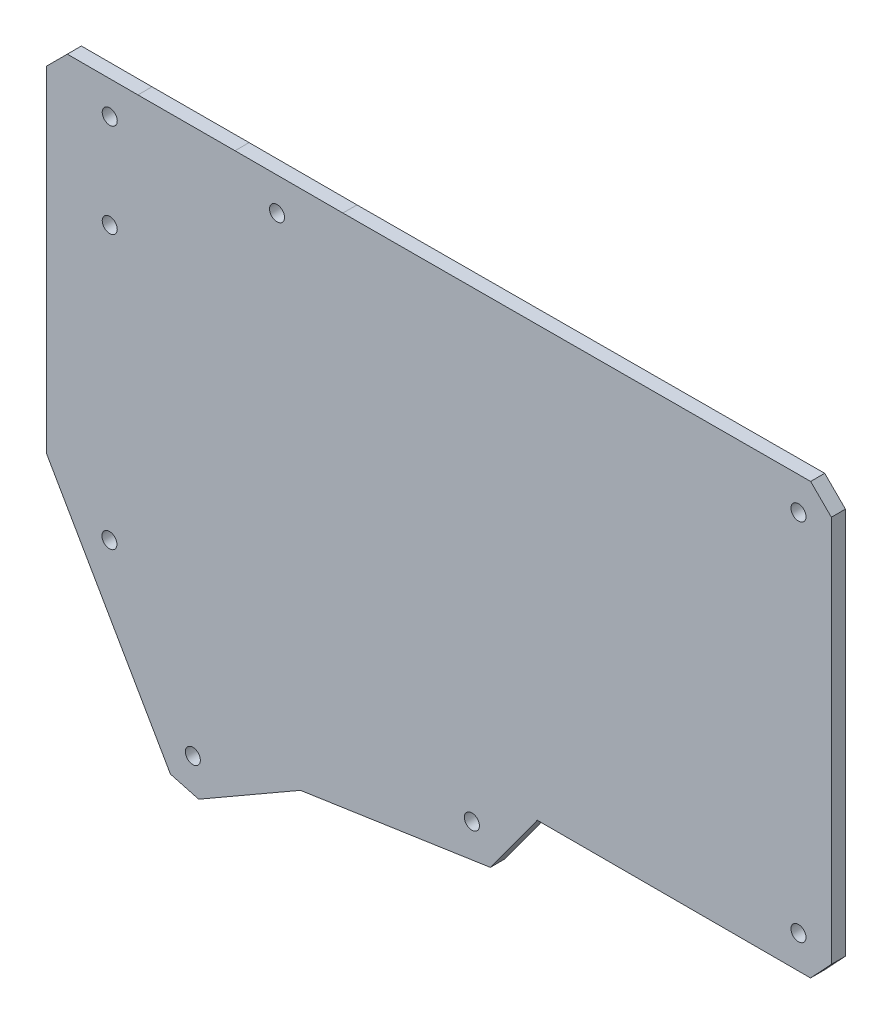
SolidWorks part; units mm, degrees
ref_plane "Plan de face" through (0, 0, 0) normal (0, 0, 1) x (1, 0, 0)
ref_plane "Plan de dessus" through (0, 0, 0) normal (0, 1, 0) x (1, 0, 0)
ref_plane "Plan de droite" through (0, 0, 0) normal (1, 0, 0) x (0, 0, -1)
sketch "Esquisse1" plane through (0, 0, 0) normal (0, 0, 1) x (1, 0, 0)
  line L0 (-117.3419, -15.4198) -> (-103.3409, -15.4198) construction
  line L1 (-103.3409, -15.4198) -> (-103.3409, -29.4208) construction
  line L2 (-103.3409, -29.4208) -> (-117.3419, -29.4208) construction
  line L3 (-117.3419, -29.4208) -> (-117.3419, -15.4198) construction
  line L4 (-98.3406, -27.0457) -> (-98.3406, -13.0447) construction
  line L5 (-98.3406, -13.0447) -> (-84.3396, -13.0447) construction
  line L6 (-84.3396, -13.0447) -> (-84.3396, -27.0457) construction
  line L7 (-84.3396, -27.0457) -> (-98.3406, -27.0457) construction
  line L8 (-79.3392, -24.6705) -> (-79.3392, -10.6695) construction
  line L9 (-79.3392, -10.6695) -> (-65.3382, -10.6695) construction
  line L10 (-65.3382, -10.6695) -> (-65.3382, -24.6705) construction
  line L11 (-65.3382, -24.6705) -> (-79.3392, -24.6705) construction
  line L12 (-60.3379, -27.0457) -> (-60.3379, -13.0447) construction
  line L13 (-60.3379, -13.0447) -> (-46.3369, -13.0447) construction
  line L14 (-46.3369, -13.0447) -> (-46.3369, -27.0457) construction
  line L15 (-46.3369, -27.0457) -> (-60.3379, -27.0457) construction
  line L16 (-41.3365, -31.796) -> (-41.3365, -17.795) construction
  line L17 (-41.3365, -17.795) -> (-27.3355, -17.795) construction
  line L18 (-27.3355, -17.795) -> (-27.3355, -31.796) construction
  line L19 (-27.3355, -31.796) -> (-41.3365, -31.796) construction
  line L20 (-22.3347, -31.796) -> (-22.3347, -17.795) construction
  line L21 (-22.3347, -17.795) -> (-8.3337, -17.795) construction
  line L22 (-8.3337, -17.795) -> (-8.3337, -31.796)
  line L23 (-8.3337, -31.796) -> (-22.3347, -31.796) construction
  line L24 (-117.3419, -34.4212) -> (-103.3409, -34.4212) construction
  line L25 (-103.3409, -34.4212) -> (-103.3409, -48.4222) construction
  line L26 (-103.3409, -48.4222) -> (-117.3419, -48.4222) construction
  line L27 (-117.3419, -48.4222) -> (-117.3419, -34.4212) construction
  line L28 (-98.3406, -32.046) -> (-84.3396, -32.046) construction
  line L29 (-84.3396, -32.046) -> (-84.3396, -46.047) construction
  line L30 (-84.3396, -46.047) -> (-98.3406, -46.047) construction
  line L31 (-98.3406, -46.047) -> (-98.3406, -32.046) construction
  line L32 (-79.3392, -29.6709) -> (-65.3382, -29.6709) construction
  line L33 (-65.3382, -29.6709) -> (-65.3382, -43.6718) construction
  line L34 (-65.3382, -43.6718) -> (-79.3392, -43.6718) construction
  line L35 (-79.3392, -43.6718) -> (-79.3392, -29.6709) construction
  line L36 (-60.3379, -32.046) -> (-46.3369, -32.046) construction
  line L37 (-46.3369, -32.046) -> (-46.3369, -46.047) construction
  line L38 (-46.3369, -46.047) -> (-60.3379, -46.047) construction
  line L39 (-60.3379, -46.047) -> (-60.3379, -32.046) construction
  line L40 (-41.3365, -36.7964) -> (-27.3355, -36.7964) construction
  line L41 (-27.3355, -36.7964) -> (-27.3355, -50.7973) construction
  line L42 (-27.3355, -50.7973) -> (-41.3365, -50.7973) construction
  line L43 (-41.3365, -50.7973) -> (-41.3365, -36.7964) construction
  line L44 (-22.3347, -36.7964) -> (-8.3337, -36.7964) construction
  line L45 (-8.3337, -36.7964) -> (-8.3337, -50.7973) construction
  line L46 (-8.3337, -50.7973) -> (-22.3347, -50.7973) construction
  line L47 (-22.3347, -50.7973) -> (-22.3347, -36.7964) construction
  line L48 (-22.3347, -55.7977) -> (-8.3337, -55.7977) construction
  line L49 (-8.3337, -55.7977) -> (-8.3337, -69.7987) construction
  line L50 (-8.3337, -69.7987) -> (-22.3347, -69.7987) construction
  line L51 (-22.3347, -69.7987) -> (-22.3347, -55.7977) construction
  line L52 (-41.3365, -55.7977) -> (-27.3355, -55.7977) construction
  line L53 (-27.3355, -55.7977) -> (-27.3355, -69.7987) construction
  line L54 (-27.3355, -69.7987) -> (-41.3365, -69.7987) construction
  line L55 (-41.3365, -69.7987) -> (-41.3365, -55.7977) construction
  line L56 (-60.3379, -51.0474) -> (-46.3369, -51.0474) construction
  line L57 (-46.3369, -51.0474) -> (-46.3369, -65.0484) construction
  line L58 (-46.3369, -65.0484) -> (-60.3379, -65.0484) construction
  line L59 (-60.3379, -65.0484) -> (-60.3379, -51.0474) construction
  line L60 (-79.3392, -48.6722) -> (-65.3382, -48.6722) construction
  line L61 (-65.3382, -48.6722) -> (-65.3382, -62.6732) construction
  line L62 (-65.3382, -62.6732) -> (-79.3392, -62.6732) construction
  line L63 (-79.3392, -62.6732) -> (-79.3392, -48.6722) construction
  line L64 (-98.3406, -51.0474) -> (-84.3396, -51.0474) construction
  line L65 (-84.3396, -51.0474) -> (-84.3396, -65.0484) construction
  line L66 (-84.3396, -65.0484) -> (-98.3406, -65.0484) construction
  line L67 (-98.3406, -65.0484) -> (-98.3406, -51.0474) construction
  line L68 (-117.3419, -53.4225) -> (-103.3409, -53.4225) construction
  line L69 (-103.3409, -53.4225) -> (-103.3409, -67.4235) construction
  line L70 (-103.3409, -67.4235) -> (-117.3419, -67.4235) construction
  line L71 (-117.3419, -67.4235) -> (-117.3419, -53.4225) construction
  line L72 (-88.8399, -70.6738) -> (-74.8389, -70.6738) construction
  line L73 (-74.8389, -70.6738) -> (-74.8389, -84.6747) construction
  line L74 (-74.8389, -84.6747) -> (-88.8399, -84.6747) construction
  line L75 (-88.8399, -84.6747) -> (-88.8399, -70.6738) construction
  line L76 (-111.4175, -75.4665) -> (-97.8899, -71.8565) construction
  line L77 (-97.8899, -71.8565) -> (-94.28, -85.3841) construction
  line L78 (-94.28, -85.3841) -> (-107.8075, -88.9941) construction
  line L79 (-107.8075, -88.9941) -> (-111.4175, -75.4665) construction
  line L80 (-134.6581, -81.5997) -> (-122.5281, -74.6075) construction
  line L81 (-122.5281, -74.6075) -> (-115.5359, -86.7375) construction
  line L82 (-115.5359, -86.7375) -> (-127.6659, -93.7297) construction
  line L83 (-127.6659, -93.7297) -> (-134.6581, -81.5997) construction
  line L86 (-6.3391, -71.9336) -> (-62.0853, -71.9336) construction
  line L89 (-72.824, -86.6446) -> (-62.0853, -71.9336) construction
  line L96 (-109.7697, -91.4639) -> (-73.0906, -86.6918) construction
  line L97 (-124.664, -99.8297) -> (-110.3971, -91.5881) construction
  line L98 (-139.9408, -76.5013) -> (-126.7151, -99.4281) construction
  line L99 (-119.8527, -15.5421) -> (-139.6028, -15.5421) construction
  line L100 (-100.8528, -13.2921) -> (-118.8527, -13.2921) construction
  line L101 (-63.8455, -8.5421) -> (-80.8528, -8.5421) construction
  line L102 (-44.8455, -10.792) -> (-62.8485, -10.792) construction
  line L103 (-25.8456, -15.5421) -> (-43.8486, -15.5421) construction
  line L104 (-6.8456, -15.5421) -> (-23.8529, -15.5421) construction
  line L105 (-6.2741, -71.3672) -> (-6.2741, -16.1136) construction
  line L106 (-23.8529, -71.9423) -> (-6.8456, -71.9423) construction
  line L107 (-61.8455, -71.9423) -> (-25.8456, -71.9423) construction
  line L108 (-72.6738, -86.4911) -> (-62.1363, -72.0583) construction
  line L109 (-140.1743, -16.1136) -> (-140.1743, -75.5958) construction
  line L110 (-134.3462, 1.5705) -> (-134.3466, -55.7217) construction
  line L111 (-134.3466, -55.7217) -> (-160.479, -70.8411) construction
  line L112 (-160.479, -70.8411) -> (-133.7613, -117.344) construction
  line L113 (-126.937, -119.1852) -> (-105.0783, -106.604) construction
  line L114 (-105.0783, -106.604) -> (-64.4097, -100.5586) construction
  line L115 (-64.4097, -100.5586) -> (-54.4636, -86.9336) construction
  line L116 (3.6609, -86.9336) -> (-54.4636, -86.9336) construction
  line L117 (8.6609, -81.591) -> (8.6609, 1.6823) construction
  line L122 (3.6609, 6.6672) -> (-96.3687, 6.3642) construction
  line L129 (8.6609, -86.9336) -> (8.6609, -0.337) construction
  line L130 (-48.3676, 6.5096) -> (-96.3687, 6.3642) construction
  line L131 (-115.3458, 1.5705) -> (-134.3462, 1.5705) construction
  line L132 (-160.479, -3.4295) -> (-160.479, -70.8411) construction
  line L134 (-119.3456, 1.5429) -> (-119.3464, -12.4295) construction
  line L136 (-140.0228, -78.3428) -> (-140.0228, 1.5705) construction
  line L138 (-160.479, -70.8411) -> (-131.2704, -121.6794) construction
  line L139 (-131.2704, -121.6794) -> (-105.0783, -106.604) construction
  line L140 (-133.7613, -117.344) -> (-126.937, -119.1852) construction
  line L142 (8.6609, 1.6823) -> (3.6609, 6.6672) construction
  line L143 (8.6609, -86.9336) -> (-54.4636, -86.9336) construction
  line L144 (8.6609, -81.591) -> (3.6609, -86.9336) construction
  line L147 (-103.3652, 6.3642) -> (-96.3687, 6.3642) construction
  line L148 (-103.3652, 6.3642) -> (-119.3456, 6.3642) construction
  line L149 (-119.3456, 6.3642) -> (-119.3456, 1.5429) construction
  line L150 (-140.0228, 1.5705) -> (-140.0228, 6.3209) construction
  line L151 (-140.0228, 6.3209) -> (-155.479, 6.3209) construction
  line L152 (-160.479, 1.3209) -> (-160.479, -3.4295) construction
  line L153 (-155.479, 6.3209) -> (-160.479, 1.3209) construction
  line L154 (8.6609, -1.3177) -> (-119.3458, -1.7055) construction
  line L155 (-146.0924, -79.8227) -> (-128.3223, -110.752) construction
  line L156 (-128.3223, -110.752) -> (-107.7547, -98.9139) construction
  line L157 (-140.0228, -78.3428) -> (-126.1111, -102.5565) construction
  line L158 (-126.1111, -102.5565) -> (-109.762, -93.1464) construction
  line L159 (-109.762, -93.1464) -> (-72.2631, -87.5722) construction
  line L160 (-72.2631, -87.5722) -> (-61.5772, -72.9336) construction
  line L161 (-5.3391, -72.9336) -> (-61.5772, -72.9336) construction
  line L162 (-5.3391, -72.9336) -> (-5.3391, -14.337) construction
  line L163 (-5.3391, -14.337) -> (-43.3418, -14.337) construction
  line L164 (-43.3418, -14.337) -> (-43.3418, -9.7225) construction
  line L165 (-43.3418, -9.7225) -> (-62.3174, -9.781) construction
  line L166 (-62.3174, -9.781) -> (-62.3244, -7.5328) construction
  line L167 (-62.3244, -7.5328) -> (-82.3255, -7.5934) construction
  line L168 (-82.3255, -7.5934) -> (-82.3183, -9.9293) construction
  line L169 (-82.3183, -9.9293) -> (-101.3458, -9.9293) construction
  line L170 (-101.3458, -9.9293) -> (-101.3458, -12.4295) construction
  line L171 (-101.3458, -12.4295) -> (-119.3464, -12.4295) construction
  line L172 (-120.3463, -12.4295) -> (-120.3466, -63.7961) construction
  line L173 (-120.3466, -63.7961) -> (-140.5236, -75.4699) construction
  line L174 (-107.7547, -98.9139) -> (-68.8973, -93.1378) construction
  line L175 (-68.8973, -93.1378) -> (-58.5285, -78.9336) construction
  line L176 (0.6609, -78.9336) -> (-58.5285, -78.9336) construction
  line L177 (0.6609, -78.9336) -> (0.6609, -1.3419) construction
  line L178 (-62.3425, -1.5328) -> (-82.3437, -1.5934) construction
  line L179 (0.6609, -78.9336) -> (0.6609, -14.337) construction
  line L180 (-146.0228, -76.3355) -> (-146.0228, 1.5705) construction
  line L181 (-140.0228, -76.3355) -> (-140.0228, 1.5705) construction
  line L183 (-140.0228, 6.3209) -> (-119.3456, 6.3642) construction
  line L184 (-120.3463, -12.4295) -> (-120.3466, -64.3728) construction
  line L185 (-119.8474, -63.5072) -> (-140.5236, -75.4699) construction
  line L186 (-101.3458, -12.4295) -> (-120.3463, -12.4295) construction
  line L187 (-140.8899, -76.8336) -> (-126.1111, -102.5565) construction
  line L188 (-146.0228, -4.8879) -> (-143.2428, -3.2829) construction
  line L189 (-143.2428, -3.2829) -> (-143.2428, -0.0728) construction
  line L190 (-143.2428, -0.0728) -> (-146.0228, 1.5322) construction
  line L191 (-146.0228, 1.5322) -> (-148.8028, -0.0728) construction
  line L192 (-148.8028, -0.0728) -> (-148.8028, -3.2829) construction
  line L193 (-148.8028, -3.2829) -> (-146.0228, -4.8879) construction
  line L194 (-110.3971, -4.8884) -> (-107.6171, -3.2834) construction
  line L195 (-107.6171, -3.2834) -> (-107.6171, -0.0733) construction
  line L196 (-107.6171, -0.0733) -> (-110.3971, 1.5317) construction
  line L197 (-110.3971, 1.5317) -> (-113.1771, -0.0733) construction
  line L198 (-113.1771, -0.0733) -> (-113.1771, -3.2834) construction
  line L199 (-113.1771, -3.2834) -> (-110.3971, -4.8884) construction
  line L200 (0.6609, -4.552) -> (3.4409, -2.947) construction
  line L201 (3.4409, -2.947) -> (3.4409, 0.2631) construction
  line L202 (3.4409, 0.2631) -> (0.6609, 1.8681) construction
  line L203 (0.6609, 1.8681) -> (-2.1191, 0.2631) construction
  line L204 (-2.1191, 0.2631) -> (-2.1191, -2.947) construction
  line L205 (-2.1191, -2.947) -> (0.6609, -4.552) construction
  line L206 (0.6609, -75.7236) -> (-2.1191, -77.3286) construction
  line L207 (-2.1191, -77.3286) -> (-2.1191, -80.5387) construction
  line L208 (-2.1191, -80.5387) -> (0.6609, -82.1437) construction
  line L209 (0.6609, -82.1437) -> (3.4409, -80.5387) construction
  line L210 (3.4409, -80.5387) -> (3.4409, -77.3286) construction
  line L211 (3.4409, -77.3286) -> (0.6609, -75.7236) construction
  line L212 (-70.6661, -90.459) -> (-72.1016, -93.3302) construction
  line L213 (-72.1016, -93.3302) -> (-70.3329, -96.009) construction
  line L217 (-6.3391, -71.9336) -> (-6.3391, -15.337) construction
  line L220 (-6.3391, -15.337) -> (-44.3418, -15.337) construction
  line L221 (-44.3418, -15.337) -> (-44.3418, -10.7256) construction
  line L222 (-44.3418, -10.7256) -> (-63.3143, -10.7841) construction
  line L223 (-63.3143, -10.7841) -> (-63.3213, -8.5358) construction
  line L224 (-63.3213, -8.5358) -> (-81.3225, -8.5903) construction
  line L225 (-81.3225, -8.5903) -> (-81.3152, -10.9293) construction
  line L226 (-81.3152, -10.9293) -> (-100.3458, -10.9293) construction
  line L227 (-100.3458, -10.9293) -> (-100.3458, -13.4295) construction
  line L228 (-100.3458, -13.4295) -> (-119.3463, -13.4295) construction
  line L231 (-119.3463, -13.4295) -> (-119.3466, -64.3728) construction
  line L232 (-119.3466, -64.3728) -> (-140.0228, -76.3355) construction
  line L233 (-140.0228, -76.3355) -> (-125.7426, -101.1906) construction
  line L234 (-125.7426, -101.1906) -> (-110.0965, -92.1851) construction
  line L235 (-110.0965, -92.1851) -> (-72.824, -86.6446) construction
  line L236 (-70.3329, -96.009) -> (-67.1286, -95.8166) construction
  line L237 (-67.1286, -95.8166) -> (-65.693, -92.9454) construction
  line L238 (-65.693, -92.9454) -> (-67.4618, -90.2666) construction
  line L239 (-67.4618, -90.2666) -> (-70.6661, -90.459) construction
  line L240 (-129.9214, -107.9687) -> (-131.5323, -110.7453) construction
  line L241 (-131.5323, -110.7453) -> (-129.9331, -113.5286) construction
  line L242 (-129.9331, -113.5286) -> (-126.7231, -113.5354) construction
  line L243 (-126.7231, -113.5354) -> (-125.1122, -110.7588) construction
  line L244 (-125.1122, -110.7588) -> (-126.7114, -107.9754) construction
  line L245 (-126.7114, -107.9754) -> (-129.9214, -107.9687) construction
  line L246 (-144.4932, -82.606) -> (-142.8823, -79.8294) construction
  line L247 (-142.8823, -79.8294) -> (-144.4815, -77.0461) construction
  line L248 (-144.4815, -77.0461) -> (-147.6915, -77.0393) construction
  line L249 (-147.6915, -77.0393) -> (-149.3024, -79.8159) construction
  line L250 (-149.3024, -79.8159) -> (-147.7033, -82.5993) construction
  line L251 (-147.7033, -82.5993) -> (-144.4932, -82.606) construction
  line L252 (3.2488, 5.6659) -> (-96.3671, 5.3642)
  line L253 (-103.3652, 5.3642) -> (-96.3671, 5.3642)
  line L254 (-103.3652, 5.3642) -> (-119.3446, 5.3642)
  line L255 (-140.0218, 5.3209) -> (-119.3446, 5.3642)
  line L256 (-140.0218, 5.3209) -> (-155.0648, 5.3209)
  line L257 (-155.0648, 5.3209) -> (-159.479, 0.9066)
  line L258 (-159.479, 0.9066) -> (-159.479, -3.4295)
  line L259 (-159.479, -3.4295) -> (-159.479, -70.5743)
  line L260 (-159.479, -70.5743) -> (-133.1007, -116.4865)
  line L261 (-133.1007, -116.4865) -> (-127.0766, -118.1118)
  line L262 (-127.0766, -118.1118) -> (-105.4129, -105.6427)
  line L263 (-105.4129, -105.6427) -> (-64.9706, -99.631)
  line L264 (-64.9706, -99.631) -> (-54.9717, -85.9336)
  line L265 (3.2271, -85.9336) -> (-54.9717, -85.9336)
  line L266 (7.6609, -81.1961) -> (3.2271, -85.9336)
  line L267 (7.6609, -81.1961) -> (7.6609, 1.2672)
  line L268 (7.6609, 1.2672) -> (3.2488, 5.6659)
  line L328 (-48.3607, 4.2621) -> (-48.3676, 6.5096) construction
  line L329 (-29.3418, 4.3208) -> (-48.3607, 4.2621) construction
  line L330 (-29.3418, -0.337) -> (-29.3418, 4.3208) construction
  line L331 (8.6609, -0.337) -> (-29.3418, -0.337) construction
  line L332 (-115.3458, 4.0707) -> (-115.3458, 1.5705) construction
  line L333 (-96.3616, 4.0707) -> (-115.3458, 4.0707) construction
  line L334 (-96.3687, 6.3642) -> (-96.3616, 4.0707) construction
  circle A2 centre (0.6609, -1.3419) radius 1.6
  circle A3 centre (0.6609, -1.3419) radius 3 construction
  circle A4 centre (-110.3971, -1.6784) radius 1.6
  circle A5 centre (0.6609, -78.9336) radius 1.6
  circle A6 centre (-68.8973, -93.1378) radius 1.6
  circle A7 centre (-128.3223, -110.752) radius 1.6
  circle A8 centre (-146.0924, -79.8227) radius 1.6
  circle A9 centre (-146.0228, -1.6779) radius 1.6
  circle A10 centre (-146.0228, -1.6779) radius 2.78 construction
  circle A11 centre (-110.3971, -1.6784) radius 2.78 construction
  circle A12 centre (0.6609, -1.3419) radius 2.78 construction
  circle A13 centre (0.6609, -78.9336) radius 2.78 construction
  circle A14 centre (-68.8973, -93.1378) radius 2.78 construction
  circle A15 centre (-128.3223, -110.752) radius 2.78 construction
  circle A16 centre (-146.0924, -79.8227) radius 2.78 construction
  circle A17 centre (-146.0228, -21.6779) radius 1.6
  point P138 (-160.479, 1.5705)
  point P139 (8.6609, 6.6823)
  point P150 (-160.479, 6.3209)
  point P197 (3.4409, -1.3419)
  dimension "D3" = 3.2
  dimension "D4" = 6
  dimension "D6" = 3.2
  dimension "D7" = 3.2
  dimension "D8" = 3.2
  dimension "D9" = 3.2
  dimension "D10" = 3.2
  dimension "D15" = 3.2
  dimension "D24" = 3.2
  dimension "D2" = 6
  dimension "D1" = 15
  dimension "D16" = 5.56
  dimension "D17" = 5.56
  dimension "D18" = 5.56
  dimension "D19" = 5.56
  dimension "D20" = 5.56
  dimension "D21" = 5.56
  dimension "D22" = 5.56
  dimension "D25" = 20
  dimension "D5" = 1
  dimension "D13" = 6
  dimension "D23" = 1
extrude "Boss.-Extru.1" add sketch "Esquisse1" along normal blind 3
